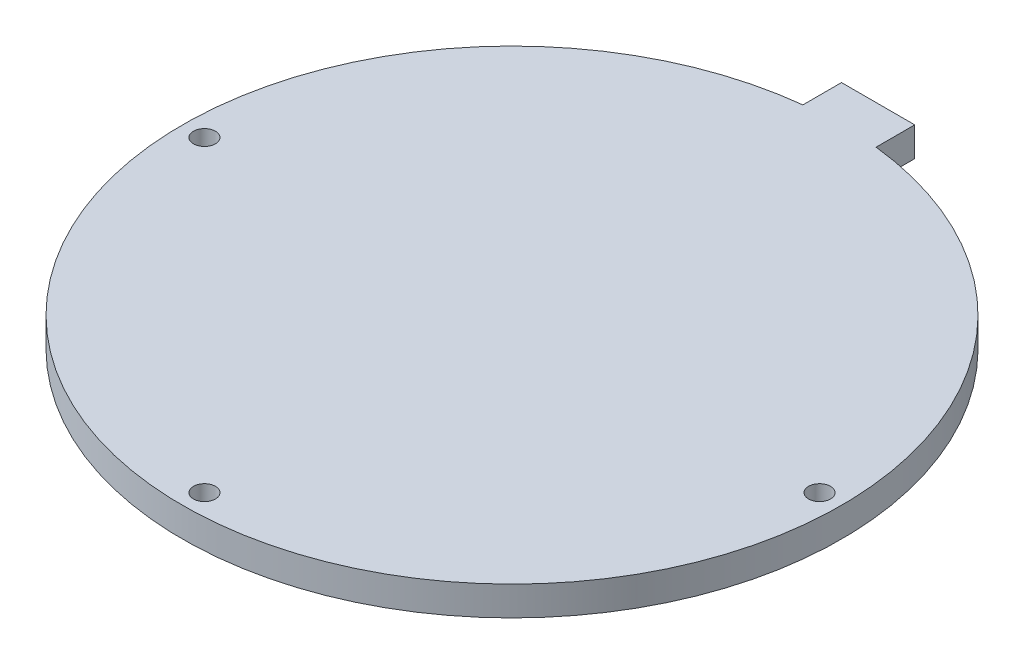
SolidWorks part; units mm, degrees
ref_plane "前视基准面" through (0, 0, 0) normal (0, 0, 1) x (1, 0, 0)
ref_plane "上视基准面" through (0, 0, 0) normal (0, 1, 0) x (1, 0, 0)
ref_plane "右视基准面" through (0, 0, 0) normal (1, 0, 0) x (0, 0, -1)
sketch "草图1" plane through (0, 0, 0) normal (0, 1, 0) x (1, 0, 0)
  line L0 (0, 0) -> (0, -42) construction
  line L1 (-5, 50) -> (5, 50)
  line L2 (-5, 50) -> (-5, 44.7214)
  line L4 (5, 50) -> (5, 44.7214)
  line L5 (-42, 0) -> (0, 0) construction
  line L6 (42, 0) -> (0, 0) construction
  arc A0 (-5, 44.7214) -> (5, 44.7214) centre (0, 0) ccw
  circle A1 centre (-42, 0) radius 1.5
  circle A2 centre (42, 0) radius 1.5
  circle A3 centre (0, -42) radius 1.5
  dimension "D1" = 90
  dimension "D5" = 3
  dimension "D2" = 50
  dimension "D3" = 10
  dimension "D4" = 42
  dimension "D6" = 42
  dimension "D7" = 42
extrude "凸台-拉伸1" add sketch "草图1" along normal blind 4
